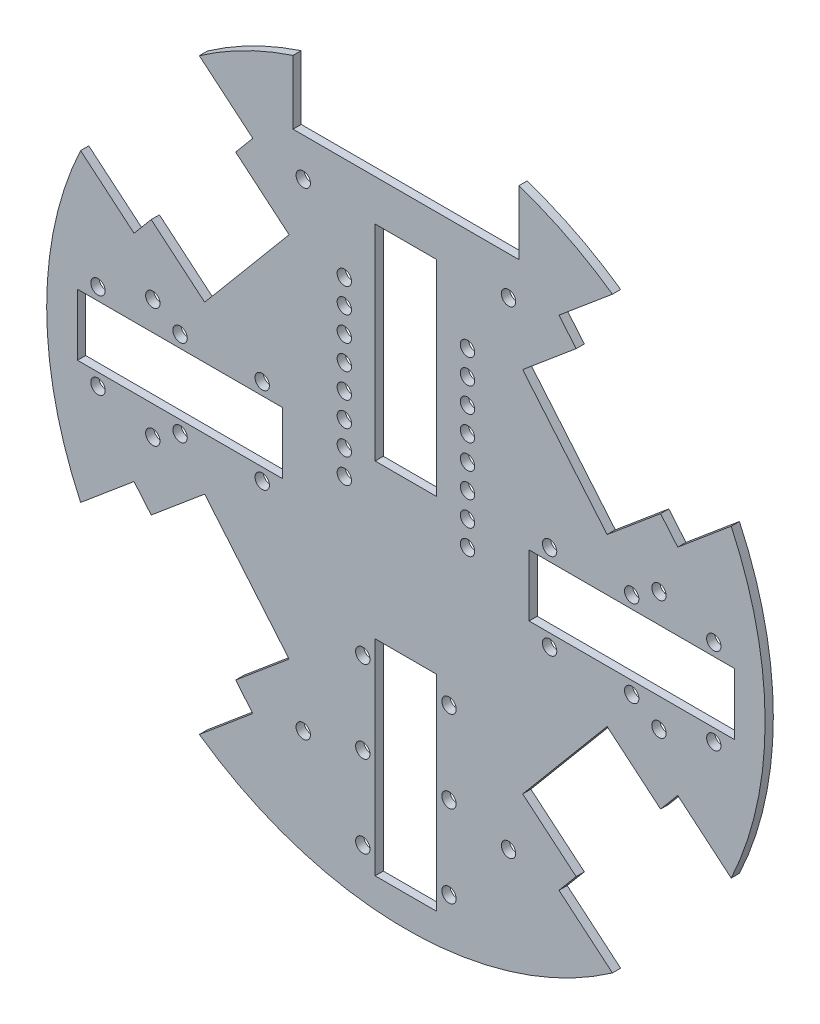
SolidWorks part; units mm, degrees
ref_plane "Front Plane" through (0, 0, 0) normal (0, 0, 1) x (1, 0, 0)
ref_plane "Top Plane" through (0, 0, 0) normal (0, 1, 0) x (1, 0, 0)
ref_plane "Right Plane" through (0, 0, 0) normal (1, 0, 0) x (0, 0, -1)
sketch "Sketch2" plane through (0, 0, 0) normal (0, 0, 1) x (1, 0, 0)
  circle A0 centre (0, 0) radius 87.5
  dimension "D1" = 175
extrude "Boss-Extrude2" add sketch "Sketch2" along normal blind 2
sketch "Sketch3" plane through (0, 0, 2) normal (0, 0, 1) x (1, 0, 0)
  line L1 (-27.5, 107.5) -> (27.5, 107.5)
  line L2 (-27.5, 107.5) -> (-27.5, 67.5)
  line L3 (-27.5, 67.5) -> (27.5, 67.5)
  line L4 (27.5, 107.5) -> (27.5, 67.5)
  line L5 (-27.5, 107.5) -> (27.5, 67.5) construction
  line L6 (-27.5, 67.5) -> (27.5, 107.5) construction
  circle A0 centre (0, 0) radius 87.5 construction
  point P2 (0, 87.5)
  dimension "D1" = 55
  dimension "D2" = 40
extrude "Cut-Extrude1" cut sketch "Sketch3" against normal through all
sketch "Sketch6" plane through (0, 0, 2) normal (0, 0, 1) x (1, 0, 0)
  line L0 (-79.2377, 37.1166) -> (-50.3122, 71.5886) construction
  line L1 (-79.2377, 37.1166) -> (-66.2149, 26.1892)
  line L2 (-50.3122, 71.5886) -> (-37.2895, 60.6612)
  line L3 (-66.2149, 26.1892) -> (-62.0368, 31.1685)
  line L5 (-62.0368, 31.1685) -> (-49.014, 20.2411)
  line L6 (-41.4676, 55.6819) -> (-28.4448, 44.7546)
  line L7 (-49.014, 20.2411) -> (-28.4448, 44.7546)
  line L8 (-64.7749, 54.3526) -> (-51.1826, 42.9473) construction
  line L9 (-51.1826, 42.9473) -> (-38.7294, 32.4978) construction
  line L10 (-41.4676, 55.6819) -> (-37.2895, 60.6612)
  line L11 (-41.4676, 55.6819) -> (-62.0368, 31.1685) construction
  line L12 (-38.7294, 32.4978) -> (0, 0) construction
  line L13 (0, 0) -> (-87.5, 0) construction
  arc A0 (-27.5, 83.0662) -> (27.5, 83.0662) centre (0, 0) ccw construction
  arc A1 (-50.3122, 71.5886) -> (-79.2377, 37.1166) centre (0, 0) ccw
  dimension "D1" = 17
  dimension "D2" = 45
  dimension "D3" = 32
  dimension "D4" = 17
  dimension "D5" = 40
extrude "Cut-Extrude2" cut sketch "Sketch6" against normal through all
sketch "Sketch7" plane through (0, 0, 2) normal (0, 0, 1) x (1, 0, 0)
  line L0 (-61.6451, 14.5223) -> (-25.0062, 58.1868) construction
  line L1 (-43.3257, 36.3546) -> (-38.7294, 32.4978) construction
  line L2 (-49.014, 20.2411) -> (-28.4448, 44.7546) construction
  circle A0 centre (-61.6451, 14.5223) radius 1.75
  circle A1 centre (-25.0062, 58.1868) radius 1.75
  dimension "D1" = 6
  dimension "D3" = 3.5
  dimension "D2" = 57
extrude "Cut-Extrude3" cut sketch "Sketch7" against normal through all
mirror "Mirror1" about plane through (0, 0, 0) normal (0, 1, 0) of "Cut-Extrude2", "Cut-Extrude3" second plane through (0, 0, 0) second plane normal (1, 0, 0)
sketch "Sketch8" plane through (0, 0, 2) normal (0, 0, 1) x (1, 0, 0)
  line L0 (0, 0) -> (-30, 0) construction
  line L1 (-80, 7.5) -> (-30, 7.5)
  line L2 (-80, 7.5) -> (-80, -7.5)
  line L3 (-80, -7.5) -> (-30, -7.5)
  line L4 (-30, 7.5) -> (-30, -7.5)
  line L5 (-80, 7.5) -> (-30, -7.5) construction
  line L6 (-80, -7.5) -> (-30, 7.5) construction
  point P0 (-55, 0)
  dimension "D1" = 15
  dimension "D2" = 50
  dimension "D3" = 30
extrude "Cut-Extrude5" cut sketch "Sketch8" against normal through all contours L2 L1 L4 L3
sketch "Sketch11" plane through (0, 0, 2) normal (0, 0, 1) x (1, 0, 0)
  line L0 (-35, -10.5) -> (-35, 10.5) construction
  line L1 (-35, 0) -> (-30, 0) construction
  line L3 (-30, 7.5) -> (-30, -7.5) construction
  circle A0 centre (-35, 10.5) radius 1.75
  circle A1 centre (-35, -10.5) radius 1.75
  dimension "D4" = 3.5
  dimension "D1" = 5
  dimension "D2" = 21
extrude "Cut-Extrude7" cut sketch "Sketch11" against normal through all
pattern_linear "LPattern2" count 3 spacing 20 along (-1, 0, 0) of "Cut-Extrude7"
pattern_circular "CirPattern1" count 3 every 90 about axis through (0, 0, 0) along (0, 0, 1) of "LPattern2", "Cut-Extrude7", "Cut-Extrude5"
sketch "Sketch13" plane through (0, 0, 2) normal (0, 0, 1) x (1, 0, 0)
  line L0 (0, 7.5) -> (0, 0) construction
  line L1 (7.5, 7.5) -> (-7.5, 7.5)
  line L2 (7.5, 7.5) -> (7.5, 57.5)
  line L3 (7.5, 57.5) -> (-7.5, 57.5)
  line L4 (-7.5, 7.5) -> (-7.5, 57.5)
  line L5 (7.5, 7.5) -> (-7.5, 57.5) construction
  line L6 (7.5, 57.5) -> (-7.5, 7.5) construction
  point P0 (0, 32.5)
  point P8 (12.2264, 57.857)
  dimension "D1" = 50
  dimension "D2" = 15
  dimension "D3" = 7.5
extrude "Cut-Extrude8" cut sketch "Sketch13" against normal through all
sketch "Sketch14" plane through (0, 0, 2) normal (0, 0, 1) x (1, 0, 0)
  line L0 (15, 42.5) -> (-15, 42.5) construction
  line L1 (0, 42.5) -> (0, 57.5) construction
  line L2 (7.5, 57.5) -> (-7.5, 57.5) construction
  line L3 (-27.5, 67.5) -> (27.5, 67.5) construction
  circle A0 centre (-15, 42.5) radius 1.75
  circle A1 centre (15, 42.5) radius 1.75
  circle A2 centre (-15, 36.5) radius 1.75
  circle A3 centre (15, 36.5) radius 1.75
  circle A4 centre (-15, 30.5) radius 1.75
  circle A5 centre (15, 30.5) radius 1.75
  circle A6 centre (-15, 24.5) radius 1.75
  circle A7 centre (15, 24.5) radius 1.75
  circle A8 centre (-15, 18.5) radius 1.75
  circle A9 centre (15, 18.5) radius 1.75
  circle A10 centre (-15, 12.5) radius 1.75
  circle A11 centre (15, 12.5) radius 1.75
  circle A12 centre (-15, 6.5) radius 1.75
  circle A13 centre (15, 6.5) radius 1.75
  circle A14 centre (-15, 0.5) radius 1.75
  circle A15 centre (15, 0.5) radius 1.75
  dimension "D3" = 3.5
  dimension "D4" = 8
  dimension "D1" = 30
  dimension "D2" = 25
extrude "Cut-Extrude9" cut sketch "Sketch14" against normal through all
